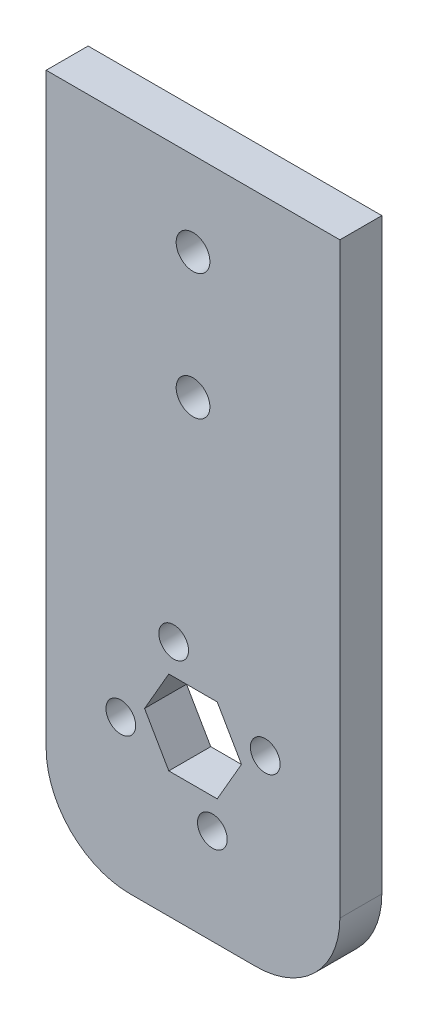
SolidWorks part; units mm, degrees
material "6061 Alloy"
ref_plane "Front Plane" through (0, 0, 0) normal (0, 0, 1) x (1, 0, 0)
ref_plane "Top Plane" through (0, 0, 0) normal (0, 1, 0) x (1, 0, 0)
ref_plane "Right Plane" through (0, 0, 0) normal (1, 0, 0) x (0, 0, -1)
sketch "Sketch1" plane through (0, 0, 0) normal (0, 0, 1) x (1, 0, 0)
  line L1 (0, 0) -> (-44.45, 0)
  line L2 (0, 0) -> (0, 101.6)
  line L3 (0, 101.6) -> (-44.45, 101.6)
  line L4 (-44.45, 0) -> (-44.45, 101.6)
  dimension "D1" = 101.6
  dimension "D2" = 44.45
extrude "Boss-Extrude2" add sketch "Sketch1" along normal blind 6.35
sketch "Sketch3" plane through (0, 0, 0) normal (0, 0, -1) x (-1, 0, 0)
  line L0 (22.225, 101.6) -> (22.225, 0) construction
  line L1 (0, 101.6) -> (44.45, 101.6) construction
  line L2 (44.45, 0) -> (0, 0) construction
  point P3 (22.225, 50.8)
fillet "Fillet1" radius 12.7 2 edges at (-44.45, 0, 3.175) (0, 0, 3.175)
hole_wizard "#7 (0.201) Diameter Hole2" positions "Sketch11" profile "Sketch12" hole size "#7" standard "ANSI Inch" end condition through all
sketch "Sketch11" plane through (0, 0, 0) normal (0, 0, -1) x (-1, 0, 0)
  line L0 (22.225, 101.6) -> (22.225, 0) construction
  line L1 (0, 101.6) -> (44.45, 101.6) construction
  point P0 (22.225, 88.9)
  point P4 (22.225, 69.85)
  dimension "D1" = 19.05
  dimension "D2" = 12.7
sketch "Sketch12" plane through (-22.225, 88.9, 0) normal (1, 0, 0) x (0, 1, 0)
  line L0 (0, 0) -> (0, 6.35)
  line L1 (0, 6.35) -> (2.5527, 6.35)
  line L2 (2.5527, 6.35) -> (2.5527, 0)
  line L5 (2.5527, 0) -> (0, 0)
  line L11 (0, -6.35) -> (0, 107.95) construction
  dimension "Thru Hole Dia." = 5.1054
  dimension "Thru Hole Depth" = 6.35
sketch "Sketch14" plane through (0, 0, 6.35) normal (0, 0, 1) x (1, 0, 0)
  line L0 (-22.225, 101.6) -> (-22.225, 0) construction
  line L1 (-14.8927, 25.4) -> (-18.5588, 31.75)
  line L2 (-18.5588, 31.75) -> (-25.8912, 31.75)
  line L3 (-25.8912, 31.75) -> (-29.5573, 25.4)
  line L4 (-29.5573, 25.4) -> (-25.8912, 19.05)
  line L5 (-25.8912, 19.05) -> (-18.5588, 19.05)
  line L6 (-18.5588, 19.05) -> (-14.8927, 25.4)
  line L7 (-31.75, 0) -> (-12.7, 0) construction
  circle A0 centre (-22.225, 25.4) radius 6.35 construction
  point P12 (-22.225, 31.75)
  dimension "D1" = 12.7
  dimension "D2" = 25.4
extrude "Cut-Extrude1" cut sketch "Sketch14" against normal through all
sketch "Sketch22" plane through (0, 0, 6.35) normal (0, 0, 1) x (1, 0, 0)
  circle A0 centre (-25.1532, 36.3282) radius 2.05
  circle A1 centre (-11.2968, 28.3282) radius 2.05
  circle A2 centre (-19.2968, 14.4718) radius 2.05
  circle A3 centre (-33.1532, 22.4718) radius 2.05
hole_wizard "M4 Clearance Hole1" positions "Sketch25" profile "Sketch24" hole size "M4" standard "ANSI Metric" end condition through all
sketch "Sketch25" plane through (0, 0, 0) normal (0, 0, -1) x (-1, 0, 0)
  point P0 (11.2968, 28.3282)
  point P3 (25.1532, 36.3282)
  point P6 (33.1532, 22.4718)
  point P9 (19.2968, 14.4718)
sketch "Sketch24" plane through (-11.2968, 28.3282, 0) normal (1, 0, 0) x (0, 1, 0)
  line L0 (0, 0) -> (0, 6.35)
  line L1 (0, 6.35) -> (2.25, 6.35)
  line L2 (2.25, 6.35) -> (2.25, 0)
  line L5 (2.25, 0) -> (0, 0)
  line L11 (0, -6.35) -> (0, 107.95) construction
  dimension "Thru Hole Dia." = 4.5
  dimension "Thru Hole Depth" = 6.35
